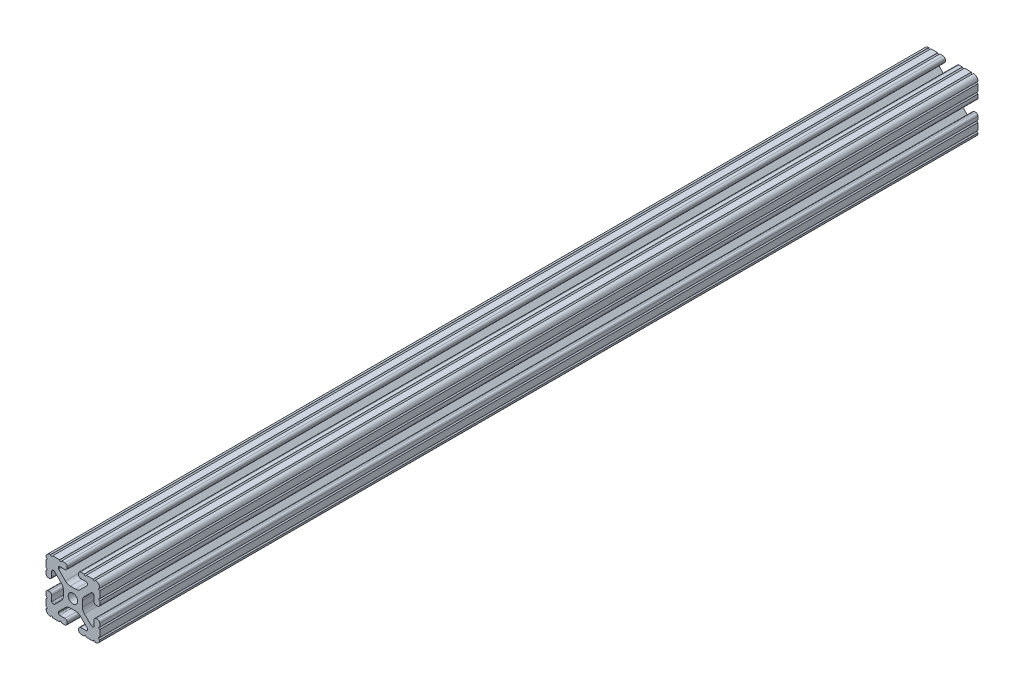
SolidWorks part; units mm, degrees
material "6105-T5 Aluminum"
ref_plane "Front Plane" through (0, 0, 0) normal (0, 0, 1) x (1, 0, 0)
ref_plane "Top Plane" through (0, 0, 0) normal (0, 1, 0) x (1, 0, 0)
ref_plane "Right Plane" through (0, 0, 0) normal (1, 0, 0) x (0, 0, -1)
sketch "Sketch1" plane through (0, 0, 0) normal (0, 0, 1) x (1, 0, 0)
  line L0 (-14.097, 10.287) -> (-13.5289, 10.287)
  line L1 (-12.9003, 10.0266) -> (-8.1292, 5.2555)
  line L2 (-6.738, 1.8969) -> (-6.738, -1.8969)
  line L3 (-8.1292, -5.2555) -> (-12.9003, -10.0266)
  line L4 (-13.5289, -10.287) -> (-14.097, -10.287)
  line L5 (-14.986, -9.398) -> (-14.986, -5.6388)
  line L6 (-16.5608, -4.064) -> (-17.4752, -4.064)
  line L7 (-19.05, -5.6388) -> (-19.05, -7.9756)
  line L8 (-19.05, -9.4996) -> (-19.05, -14.3256)
  line L9 (-19.05, -15.8496) -> (-19.05, -15.875)
  line L10 (-15.875, -19.05) -> (-15.8496, -19.05)
  line L11 (-14.3256, -19.05) -> (-9.4996, -19.05)
  line L12 (-7.9756, -19.05) -> (-5.6388, -19.05)
  line L13 (-4.064, -17.4752) -> (-4.064, -16.5608)
  line L14 (-5.6388, -14.986) -> (-9.398, -14.986)
  line L15 (-10.287, -14.097) -> (-10.287, -13.5289)
  line L16 (-10.0266, -12.9003) -> (-5.2555, -8.1292)
  line L17 (-1.8969, -6.738) -> (1.8969, -6.738)
  line L18 (5.2555, -8.1292) -> (10.0266, -12.9003)
  line L19 (10.287, -13.5289) -> (10.287, -14.097)
  line L20 (9.398, -14.986) -> (5.6388, -14.986)
  line L21 (4.064, -16.5608) -> (4.064, -17.4752)
  line L22 (5.6388, -19.05) -> (7.9756, -19.05)
  line L23 (9.4996, -19.05) -> (14.3256, -19.05)
  line L24 (15.8496, -19.05) -> (15.875, -19.05)
  line L25 (19.05, -15.875) -> (19.05, -15.8496)
  line L26 (19.05, -14.3256) -> (19.05, -9.4996)
  line L27 (19.05, -7.9756) -> (19.05, -5.6388)
  line L28 (17.4752, -4.064) -> (16.5608, -4.064)
  line L29 (14.986, -5.6388) -> (14.986, -9.398)
  line L30 (14.097, -10.287) -> (13.5289, -10.287)
  line L31 (12.9003, -10.0266) -> (8.1292, -5.2555)
  line L32 (6.738, -1.8969) -> (6.738, 1.8969)
  line L33 (8.1292, 5.2555) -> (12.9003, 10.0266)
  line L34 (13.5289, 10.287) -> (14.097, 10.287)
  line L35 (14.986, 9.398) -> (14.986, 5.6388)
  line L36 (16.5608, 4.064) -> (17.4752, 4.064)
  line L37 (19.05, 5.6388) -> (19.05, 7.9756)
  line L38 (19.05, 9.4996) -> (19.05, 14.3256)
  line L39 (19.05, 15.8496) -> (19.05, 15.875)
  line L40 (15.875, 19.05) -> (15.8496, 19.05)
  line L41 (14.3256, 19.05) -> (9.4996, 19.05)
  line L42 (7.9756, 19.05) -> (5.6388, 19.05)
  line L43 (4.064, 17.4752) -> (4.064, 16.5608)
  line L44 (5.6388, 14.986) -> (9.398, 14.986)
  line L45 (10.287, 14.097) -> (10.287, 13.5289)
  line L46 (10.0266, 12.9003) -> (5.2555, 8.1292)
  line L47 (1.8969, 6.738) -> (-1.8969, 6.738)
  line L48 (-5.2555, 8.1292) -> (-10.0266, 12.9003)
  line L49 (-10.287, 13.5289) -> (-10.287, 14.097)
  line L50 (-9.398, 14.986) -> (-5.6388, 14.986)
  line L51 (-4.064, 16.5608) -> (-4.064, 17.4752)
  line L52 (-5.6388, 19.05) -> (-7.9756, 19.05)
  line L53 (-9.4996, 19.05) -> (-14.3256, 19.05)
  line L54 (-15.8496, 19.05) -> (-15.875, 19.05)
  line L55 (-19.05, 15.875) -> (-19.05, 15.8496)
  line L56 (-19.05, 14.3256) -> (-19.05, 9.4996)
  line L57 (-19.05, 7.9756) -> (-19.05, 5.6388)
  line L58 (-17.4752, 4.064) -> (-16.5608, 4.064)
  line L59 (-14.986, 5.6388) -> (-14.986, 9.398)
  circle A0 centre (0, 0) radius 3.3274
  arc A1 (-14.097, 10.287) -> (-14.986, 9.398) centre (-14.097, 9.398) ccw
  arc A2 (-12.9003, 10.0266) -> (-13.5289, 10.287) centre (-13.5289, 9.398) ccw
  arc A3 (-6.738, 1.8969) -> (-8.1292, 5.2555) centre (-11.4878, 1.8969) ccw
  arc A4 (-8.1292, -5.2555) -> (-6.738, -1.8969) centre (-11.4878, -1.8969) ccw
  arc A5 (-13.5289, -10.287) -> (-12.9003, -10.0266) centre (-13.5289, -9.398) ccw
  arc A6 (-14.986, -9.398) -> (-14.097, -10.287) centre (-14.097, -9.398) ccw
  arc A7 (-14.986, -5.6388) -> (-16.5608, -4.064) centre (-16.5608, -5.6388) ccw
  arc A8 (-17.4752, -4.064) -> (-19.05, -5.6388) centre (-17.4752, -5.6388) ccw
  arc A9 (-19.05, -9.4996) -> (-19.05, -7.9756) centre (-19.05, -8.7376) ccw
  arc A10 (-19.05, -15.8496) -> (-19.05, -14.3256) centre (-19.05, -15.0876) ccw
  arc A11 (-19.05, -15.875) -> (-15.875, -19.05) centre (-15.875, -15.875) ccw
  arc A12 (-14.3256, -19.05) -> (-15.8496, -19.05) centre (-15.0876, -19.05) ccw
  arc A13 (-7.9756, -19.05) -> (-9.4996, -19.05) centre (-8.7376, -19.05) ccw
  arc A14 (-5.6388, -19.05) -> (-4.064, -17.4752) centre (-5.6388, -17.4752) ccw
  arc A15 (-4.064, -16.5608) -> (-5.6388, -14.986) centre (-5.6388, -16.5608) ccw
  arc A16 (-10.287, -14.097) -> (-9.398, -14.986) centre (-9.398, -14.097) ccw
  arc A17 (-10.0266, -12.9003) -> (-10.287, -13.5289) centre (-9.398, -13.5289) ccw
  arc A18 (-1.8969, -6.738) -> (-5.2555, -8.1292) centre (-1.8969, -11.4878) ccw
  arc A19 (5.2555, -8.1292) -> (1.8969, -6.738) centre (1.8969, -11.4878) ccw
  arc A20 (10.287, -13.5289) -> (10.0266, -12.9003) centre (9.398, -13.5289) ccw
  arc A21 (9.398, -14.986) -> (10.287, -14.097) centre (9.398, -14.097) ccw
  arc A22 (5.6388, -14.986) -> (4.064, -16.5608) centre (5.6388, -16.5608) ccw
  arc A23 (4.064, -17.4752) -> (5.6388, -19.05) centre (5.6388, -17.4752) ccw
  arc A24 (9.4996, -19.05) -> (7.9756, -19.05) centre (8.7376, -19.05) ccw
  arc A25 (15.8496, -19.05) -> (14.3256, -19.05) centre (15.0876, -19.05) ccw
  arc A26 (15.875, -19.05) -> (19.05, -15.875) centre (15.875, -15.875) ccw
  arc A27 (19.05, -14.3256) -> (19.05, -15.8496) centre (19.05, -15.0876) ccw
  arc A28 (19.05, -7.9756) -> (19.05, -9.4996) centre (19.05, -8.7376) ccw
  arc A29 (19.05, -5.6388) -> (17.4752, -4.064) centre (17.4752, -5.6388) ccw
  arc A30 (16.5608, -4.064) -> (14.986, -5.6388) centre (16.5608, -5.6388) ccw
  arc A31 (14.097, -10.287) -> (14.986, -9.398) centre (14.097, -9.398) ccw
  arc A32 (12.9003, -10.0266) -> (13.5289, -10.287) centre (13.5289, -9.398) ccw
  arc A33 (6.738, -1.8969) -> (8.1292, -5.2555) centre (11.4878, -1.8969) ccw
  arc A34 (8.1292, 5.2555) -> (6.738, 1.8969) centre (11.4878, 1.8969) ccw
  arc A35 (13.5289, 10.287) -> (12.9003, 10.0266) centre (13.5289, 9.398) ccw
  arc A36 (14.986, 9.398) -> (14.097, 10.287) centre (14.097, 9.398) ccw
  arc A37 (14.986, 5.6388) -> (16.5608, 4.064) centre (16.5608, 5.6388) ccw
  arc A38 (17.4752, 4.064) -> (19.05, 5.6388) centre (17.4752, 5.6388) ccw
  arc A39 (19.05, 9.4996) -> (19.05, 7.9756) centre (19.05, 8.7376) ccw
  arc A40 (19.05, 15.8496) -> (19.05, 14.3256) centre (19.05, 15.0876) ccw
  arc A41 (19.05, 15.875) -> (15.875, 19.05) centre (15.875, 15.875) ccw
  arc A42 (14.3256, 19.05) -> (15.8496, 19.05) centre (15.0876, 19.05) ccw
  arc A43 (7.9756, 19.05) -> (9.4996, 19.05) centre (8.7376, 19.05) ccw
  arc A44 (5.6388, 19.05) -> (4.064, 17.4752) centre (5.6388, 17.4752) ccw
  arc A45 (4.064, 16.5608) -> (5.6388, 14.986) centre (5.6388, 16.5608) ccw
  arc A46 (10.287, 14.097) -> (9.398, 14.986) centre (9.398, 14.097) ccw
  arc A47 (10.0266, 12.9003) -> (10.287, 13.5289) centre (9.398, 13.5289) ccw
  arc A48 (1.8969, 6.738) -> (5.2555, 8.1292) centre (1.8969, 11.4878) ccw
  arc A49 (-5.2555, 8.1292) -> (-1.8969, 6.738) centre (-1.8969, 11.4878) ccw
  arc A50 (-10.287, 13.5289) -> (-10.0266, 12.9003) centre (-9.398, 13.5289) ccw
  arc A51 (-9.398, 14.986) -> (-10.287, 14.097) centre (-9.398, 14.097) ccw
  arc A52 (-5.6388, 14.986) -> (-4.064, 16.5608) centre (-5.6388, 16.5608) ccw
  arc A53 (-4.064, 17.4752) -> (-5.6388, 19.05) centre (-5.6388, 17.4752) ccw
  arc A54 (-9.4996, 19.05) -> (-7.9756, 19.05) centre (-8.7376, 19.05) ccw
  arc A55 (-15.8496, 19.05) -> (-14.3256, 19.05) centre (-15.0876, 19.05) ccw
  arc A56 (-15.875, 19.05) -> (-19.05, 15.875) centre (-15.875, 15.875) ccw
  arc A57 (-19.05, 14.3256) -> (-19.05, 15.8496) centre (-19.05, 15.0876) ccw
  arc A58 (-19.05, 7.9756) -> (-19.05, 9.4996) centre (-19.05, 8.7376) ccw
  arc A59 (-19.05, 5.6388) -> (-17.4752, 4.064) centre (-17.4752, 5.6388) ccw
  arc A60 (-16.5608, 4.064) -> (-14.986, 5.6388) centre (-16.5608, 5.6388) ccw
extrude "Boss-Extrude1" add sketch "Sketch1" along normal blind 622.3
